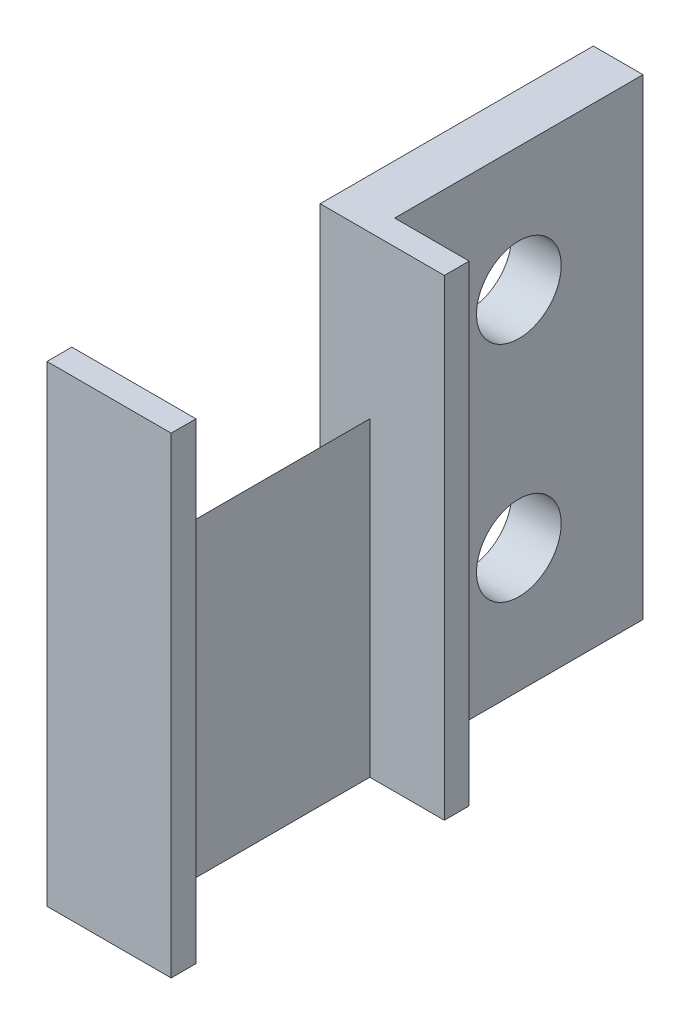
SolidWorks part; units mm, degrees
ref_plane "Front Plane" through (0, 0, 0) normal (0, 0, 1) x (1, 0, 0)
ref_plane "Top Plane" through (0, 0, 0) normal (0, 1, 0) x (1, 0, 0)
ref_plane "Right Plane" through (0, 0, 0) normal (1, 0, 0) x (0, 0, -1)
sketch "Sketch1" plane through (0, 0, 0) normal (0, 0, 1) x (1, 0, 0)
  line L0 (-2, 5) -> (2, 12.5)
  line L1 (2, 12.5) -> (2, -12.5)
  line L2 (2, -12.5) -> (-2, -12.5)
  line L3 (-2, -12.5) -> (-2, 5)
  point P2 (0, -12.5)
  point P6 (2, 0)
  dimension "D1" = 4
  dimension "D2" = 7.5
  dimension "D3" = 25
extrude "Boss-Extrude1" add sketch "Sketch1" along normal mid plane 20
sketch "Sketch2" plane through (0, -12.5, 0) normal (0, -1, 0) x (1, 0, 0)
  line L0 (-3.0311, 0) -> (3.9404, 0) construction
  line L1 (-2, 10) -> (8, 10)
  line L2 (-2, 10) -> (-2, 12)
  line L3 (-2, 12) -> (8, 12)
  line L4 (8, 10) -> (8, 12)
  line L5 (8, -10) -> (8, -12)
  line L6 (-2, -12) -> (8, -12)
  line L7 (-2, -10) -> (-2, -12)
  line L8 (-2, -10) -> (8, -10)
  dimension "D1" = 2
  dimension "D2" = 10
extrude "Boss-Extrude2" add sketch "Sketch2" against normal blind 38
sketch "Sketch4" plane through (0, 0, -12) normal (0, 0, -1) x (-1, 0, 0)
  line L0 (2, 25.5) -> (-8, 25.5) construction
  line L1 (2, -12.5) -> (-2, -12.5)
  line L2 (2, -12.5) -> (2, 25.5)
  line L3 (2, 25.5) -> (-2, 25.5)
  line L4 (-2, -12.5) -> (-2, 25.5)
  line L5 (2, 25.5) -> (2, -12.5) construction
  dimension "D1" = 4
extrude "Boss-Extrude3" add sketch "Sketch4" along normal blind 20
sketch "Sketch3" plane through (2, 0, 0) normal (1, 0, 0) x (0, 0, -1)
  line L0 (32, -12.5) -> (12, -12.5) construction
  line L1 (22, -2.5) -> (22, 15.5) construction
  line L3 (32, 25.5) -> (32, -12.5) construction
  circle A0 centre (22, -2.5) radius 3.41
  circle A1 centre (22, 15.5) radius 3.41
  point P10 (22, -12.5)
  point P13 (32, 6.5)
  point P14 (22, 6.5)
  dimension "D1" = 6.82
  dimension "D2" = 18
extrude "Cut-Extrude1" cut sketch "Sketch3" against normal up to next
equation "\"Printed Hole Size\"= 6.5"
equation "\"CAD Hole Size\"= 0.9683 * \"Printed Hole Size\" + 0.5265"
